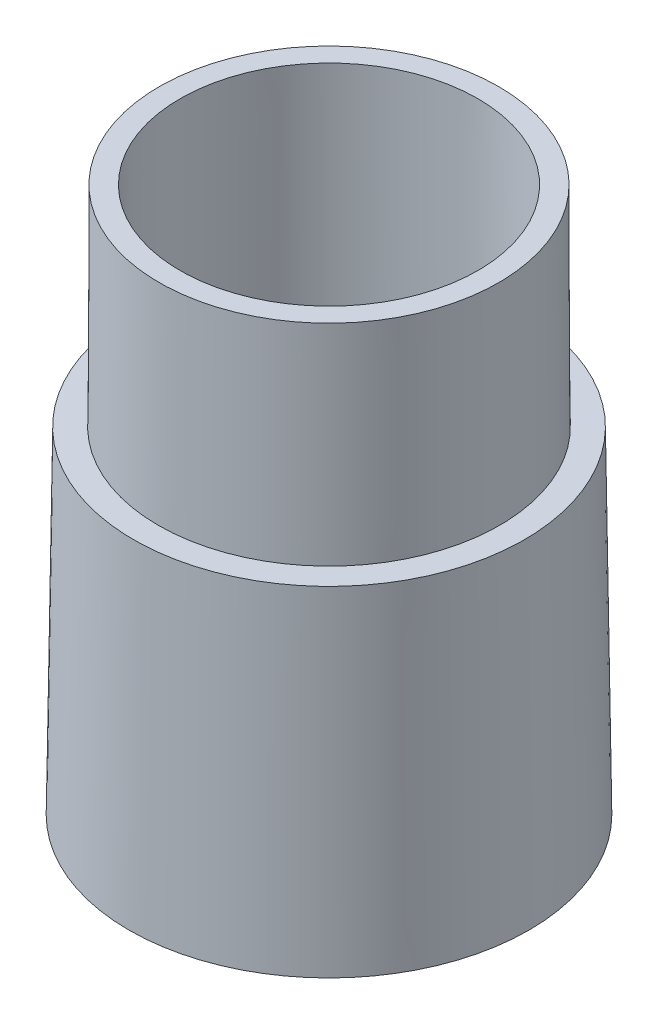
SolidWorks part; units mm, degrees
ref_plane "Front Plane" through (0, 0, 0) normal (0, 0, 1) x (1, 0, 0)
ref_plane "Top Plane" through (0, 0, 0) normal (0, 1, 0) x (1, 0, 0)
ref_plane "Right Plane" through (0, 0, 0) normal (1, 0, 0) x (0, 0, -1)
sketch "Sketch1" plane through (0, 0, 0) normal (1, 0, 0) x (0, 0, -1)
  line L0 (-9.925, 0) -> (-9.7, 16.67)
  line L1 (-9.7, 16.67) -> (-8.47, 16.67)
  line L2 (-8.47, 16.67) -> (-8.425, 27.08)
  line L3 (-8.425, 27.08) -> (-7.39, 27.08)
  line L4 (-7.39, 27.08) -> (-7.485, 14.68)
  line L5 (-7.485, 14.68) -> (-8.6119, 14.68)
  line L6 (-8.6119, 14.68) -> (-8.81, 0)
  line L7 (-8.81, 0) -> (-9.925, 0)
  line L8 (0, 0) -> (0, 12.906) construction
  point P11 (0, 0)
  dimension "D1" = 19.85
  dimension "D2" = 19.4
  dimension "D3" = 16.94
  dimension "D4" = 16.85
  dimension "D5" = 14.78
  dimension "D6" = 14.97
  dimension "D7" = 14.68
  dimension "D8" = 17.62
  dimension "D9" = 16.67
  dimension "D10" = 27.08
revolve "Revolve1" add sketch "Sketch1" angle 360 about L8
sketch "Sketch2" plane through (0, 0, 0) normal (0, -1, 0) x (1, 0, 0)
  line L0 (0, -8.81) -> (0, 8.81) construction
  circle A0 centre (0, -8.81) radius 0.25
  circle A1 centre (0, 0) radius 8.81 construction
  point P4 (0, 0)
  dimension "D1" = 0.5
sketch "Sketch3" plane through (0, 0, 0) normal (1, 0, 0) x (0, 0, -1)
  line L0 (8.81, 0) -> (8.6119, 14.68)
  line L1 (-8.6119, 14.68) -> (8.6119, 14.68) construction
  line L2 (8.81, 0) -> (8.6119, 14.68) construction
sweep "Sweep1" add profiles "Sketch2" path "Sketch3"
pattern_circular "CirPattern1" count 4 over 360 about axis through (0, 0, 0) along (0, -1, 0) of "Sweep1"
